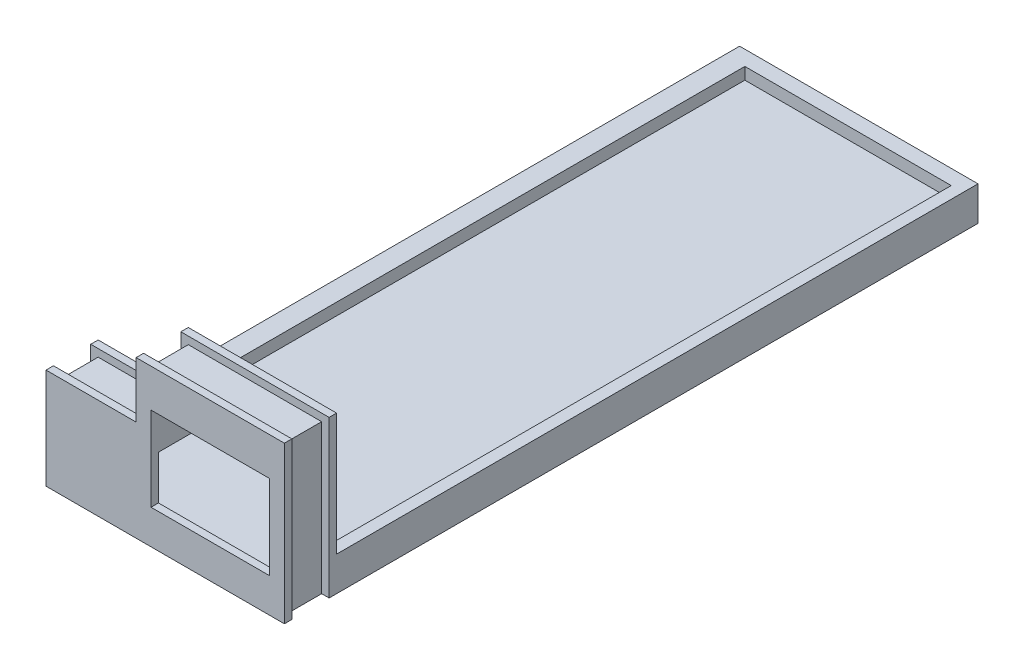
SolidWorks part; units mm, degrees
ref_plane "前视基准面" through (0, 0, 0) normal (0, 0, 1) x (1, 0, 0)
ref_plane "上视基准面" through (0, 0, 0) normal (0, 1, 0) x (1, 0, 0)
ref_plane "右视基准面" through (0, 0, 0) normal (1, 0, 0) x (0, 0, -1)
sketch "草图1" plane through (0, 0, 0) normal (0, 0, 1) x (1, 0, 0)
  line B0 (11.3913, 12.8) -> (11.3913, 1.6)
  line B1 (27.5001, 1.6) -> (27.5001, 0)
  line B2 (0, 1.6) -> (27.5001, 1.6)
  line B3 (11.3913, 12.8) -> (27.0937, 12.8)
  line B4 (27.0937, 12.8) -> (27.0937, 1.6)
  line B5 (0, 0) -> (27.5001, 0)
  line B6 (0, 1.6) -> (0, 0)
sketch_block_instance "right_board-1"
sketch_block "right_board"
sketch "草图2" plane through (0, 0, 0) normal (0, 0, 1) x (1, 0, 0)
  line L0 (11.3913, 12.8) -> (27.0937, 12.8) construction
  line L1 (11.2913, 12.9) -> (27.1937, 12.9)
  line L2 (11.2913, 12.9) -> (11.2913, 1.6)
  line L3 (11.2913, 1.6) -> (27.1937, 1.6)
  line L4 (27.1937, 12.9) -> (27.1937, 1.6)
  line L5 (11.3913, 12.8) -> (11.3913, 1.6) construction
  line L6 (27.0937, 12.8) -> (27.0937, 1.6) construction
  line L7 (0, 1.6) -> (27.5001, 1.6) construction
  line L8 (-1.8063, -3) -> (28.1937, -3)
  line L9 (28.1937, -3) -> (28.1937, 17)
  line L10 (28.1937, 17) -> (10.2913, 17)
  line L11 (10.2913, 17) -> (10.2913, 9.5)
  line L12 (10.2913, 9.5) -> (-1.8063, 9.5)
  line L13 (-1.8063, 9.5) -> (-1.8063, -3)
  dimension "D1" = 20
  dimension "D2" = 0.1
  dimension "D3" = 0.1
  dimension "D4" = 0
  dimension "D5" = 30
  dimension "D6" = 12.5
  dimension "D7" = 4.6
  dimension "D8" = 1
  dimension "D9" = 1
  dimension "D10" = 0.1
extrude "凸台-拉伸1" add sketch "草图2" along normal blind 5
sketch "草图3" plane through (0, 0, 5) normal (0, 0, 1) x (1, 0, 0)
  line L27 (-2.8063, -3) -> (29.1937, -3)
  line L32 (29.1937, -3) -> (29.1937, 18)
  line L33 (29.1937, 18) -> (9.2913, 18)
  line L34 (9.2913, 18) -> (9.2913, 10.5)
  line L35 (9.2913, 10.5) -> (-2.8063, 10.5)
  line L36 (-2.8063, 10.5) -> (-2.8063, -3)
  line L37 (29.1937, -3) -> (29.1937, 18)
  line L38 (29.1937, 18) -> (9.2913, 18)
  line L39 (9.2913, 18) -> (9.2913, 10.5)
  line L40 (9.2913, 10.5) -> (-2.8063, 10.5)
  line L41 (-2.8063, 10.5) -> (-2.8063, -3)
  dimension "D1" = 1
extrude "凸台-拉伸2" add sketch "草图3" along normal blind 1
sketch "草图5" plane through (0, 0, 0) normal (0, 0, -1) x (-1, 0, 0)
  line L71 (-29.1937, 18) -> (-29.1937, -3)
  line L72 (-29.1937, -3) -> (-28.1937, -3)
  line L73 (-28.1937, -3) -> (1.8063, -3)
  line L74 (1.8063, -3) -> (2.8063, -3)
  line L75 (2.8063, -3) -> (2.8063, 10.5)
  line L76 (2.8063, 10.5) -> (-9.2913, 10.5)
  line L77 (-9.2913, 10.5) -> (-9.2913, 18)
  line L78 (-9.2913, 18) -> (-29.1937, 18)
  line L79 (-29.1937, 18) -> (-29.1937, -3)
  line L80 (-29.1937, -3) -> (-28.1937, -3)
  line L81 (-28.1937, -3) -> (1.8063, -3)
  line L82 (1.8063, -3) -> (2.8063, -3)
  line L83 (2.8063, -3) -> (2.8063, 10.5)
  line L84 (2.8063, 10.5) -> (-9.2913, 10.5)
  line L85 (-9.2913, 10.5) -> (-9.2913, 18)
  line L86 (-9.2913, 18) -> (-29.1937, 18)
  dimension "D1" = 0
extrude "凸台-拉伸4" add sketch "草图5" along normal blind 1
sketch "草图6" plane through (0, 0, 6) normal (0, 0, 1) x (1, 0, 0)
  line L1 (27.1937, 1.6) -> (11.2913, 1.6)
  line L2 (27.1937, 1.6) -> (27.1937, 12.9)
  line L3 (27.1937, 12.9) -> (11.2913, 12.9)
  line L4 (11.2913, 1.6) -> (11.2913, 12.9)
extrude "切除-拉伸1" cut sketch "草图6" against normal through all
sketch "草图7" plane through (0, 0, -1) normal (0, 0, -1) x (-1, 0, 0)
  line L0 (0, 1.6) -> (-27.5001, 1.6) construction
  line L1 (-27.6001, 1.6) -> (0.1, 1.6)
  line L2 (-27.6001, 1.6) -> (-27.6001, 0)
  line L3 (-27.6001, 0) -> (0.1, 0)
  line L4 (0.1, 1.6) -> (0.1, 0)
  line L5 (0, 0) -> (-27.5001, 0) construction
  line L6 (-27.5001, 1.6) -> (-27.5001, 0) construction
  line L7 (0, 1.6) -> (0, 0) construction
  dimension "D1" = 0.1
  dimension "D2" = 0.1
extrude "切除-拉伸2" cut sketch "草图7" against normal blind 6
sketch "草图8" plane through (0, 0, -1) normal (0, 0, -1) x (-1, 0, 0)
  line L0 (-27.6001, 1.6) -> (-29.1937, 1.6)
  line L1 (-29.1937, 18) -> (-29.1937, -3) construction
  line L2 (-29.1937, 1.6) -> (-29.1937, -3)
  line L3 (-29.1937, -3) -> (2.8063, -3)
  line L4 (2.8063, -3) -> (2.8063, 1.6)
  line L5 (2.8063, -3) -> (2.8063, 10.5) construction
  line L6 (2.8063, 1.6) -> (0.1, 1.6)
  line L7 (0.1, 1.6) -> (0.1, 0)
  line L8 (0.1, 0) -> (-27.6001, 0)
  line L9 (-27.6001, 0) -> (-27.6001, 1.6)
extrude "凸台-拉伸5" add sketch "草图8" along normal blind 84.1
sketch "草图9" plane through (0, 0, -85.1) normal (0, 0, -1) x (-1, 0, 0)
  line L1 (-29.1937, -3) -> (2.8063, -3)
  line L2 (-29.1937, -3) -> (-29.1937, 1.6)
  line L3 (-29.1937, 1.6) -> (2.8063, 1.6)
  line L4 (2.8063, -3) -> (2.8063, 1.6)
extrude "凸台-拉伸6" add sketch "草图9" along normal blind 2
sketch "草图10" plane through (0, 0, -1) normal (0, 0, -1) x (-1, 0, 0)
  line L0 (-10.2913, 9.5) -> (1.8063, 9.5) construction
  line L1 (-11.2913, 1.6) -> (0.1, 1.6)
  line L2 (-11.2913, 1.6) -> (-11.2913, 7.5)
  line L3 (-11.2913, 7.5) -> (0.1, 7.5)
  line L4 (0.1, 1.6) -> (0.1, 7.5)
  line L5 (0.1, 1.6) -> (0.1, 0) construction
  dimension "D1" = 2
extrude "切除-拉伸3" cut sketch "草图10" against normal blind 6
